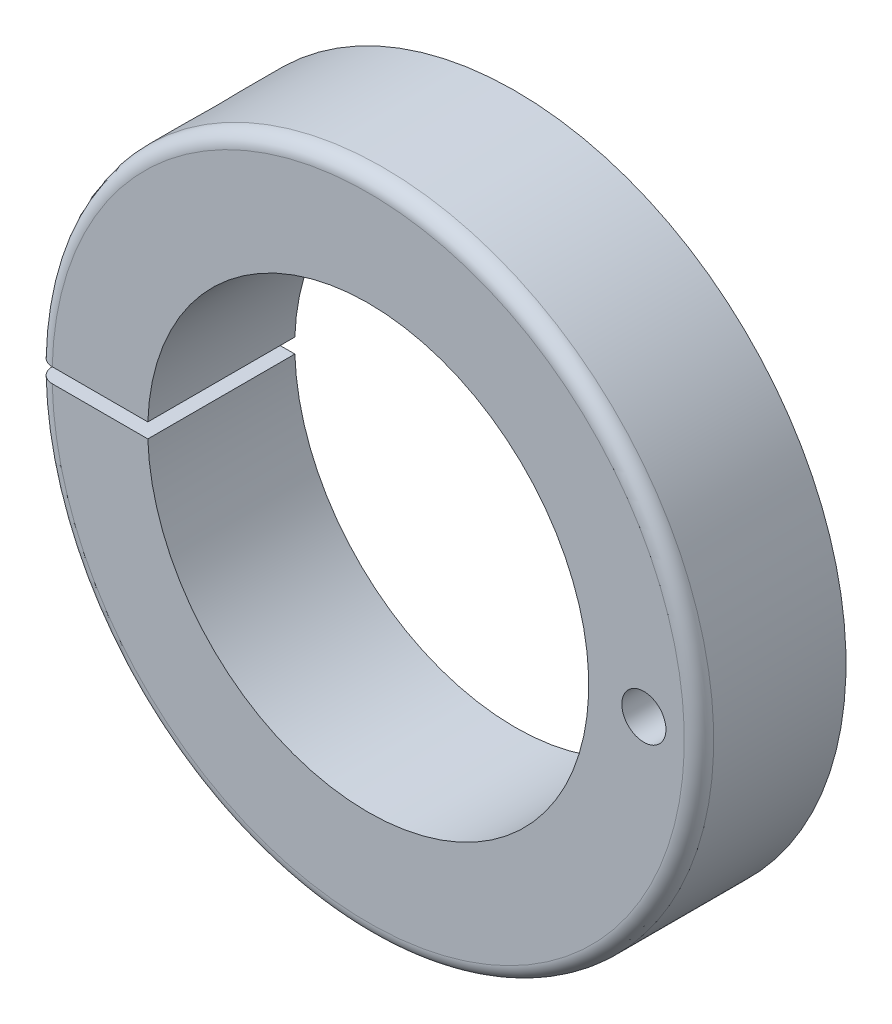
SolidWorks part; units mm, degrees
material "PW100:Mi:0:41:Ar:0:-1:C1:1:2:3:Re:15:"
ref_plane "Plan1" through (0, 0, 0) normal (0, 0, 1) x (1, 0, 0)
ref_plane "Plan2" through (0, 0, 0) normal (0, 1, 0) x (1, 0, 0)
ref_plane "Plan3" through (0, 0, 0) normal (1, 0, 0) x (0, 0, -1)
sketch "Esquisse1" plane through (0, 0, 0) normal (0, 0, 1) x (1, 0, 0)
  circle A0 centre (0, 0) radius 45
extrude "Base-Extrusion" add sketch "Esquisse1" along normal blind 20
sketch "Esquisse2" plane through (0, 0, 20) normal (0, 0, 1) x (1, 0, 0)
  circle A0 centre (0, 0) radius 30
extrude "Enlèv. mat.-Extru.1" cut sketch "Esquisse2" against normal blind 20
sketch "Esquisse3" plane through (0, 0, 20) normal (0, 0, 1) x (1, 0, 0)
  line L1 (-50, 1) -> (-20, 1)
  line L2 (-50, 1) -> (-50, -1)
  line L3 (-50, -1) -> (-20, -1)
  line L4 (-20, 1) -> (-20, -1)
extrude "Enlèv. mat.-Extru.2" cut sketch "Esquisse3" against normal blind 20
ref_plane "Plan4" through (0, 45, 0) normal (0, 1, 0) x (-1, 0, 0)
sketch "Esquisse4" plane through (0, 45, 0) normal (0, 1, 0) x (-1, 0, 0)
  circle A0 centre (37.5, 10) radius 3
extrude "Enlèv. mat.-Extru.3" cut sketch "Esquisse4" against normal through all
sketch "Esquisse5" plane through (0, 45, 0) normal (0, 1, 0) x (-1, 0, 0)
  circle A0 centre (37.5, 10) radius 7
extrude "Enlèv. mat.-Extru.4" cut sketch "Esquisse5" against normal blind 40
fillet "Congé1" radius 2
sketch "Esquisse6" plane through (0, 0, 20) normal (0, 0, 1) x (1, 0, 0)
  circle A0 centre (37.5, 0) radius 3
extrude "Enlèv. mat.-Extru.5" cut sketch "Esquisse6" against normal blind 20
